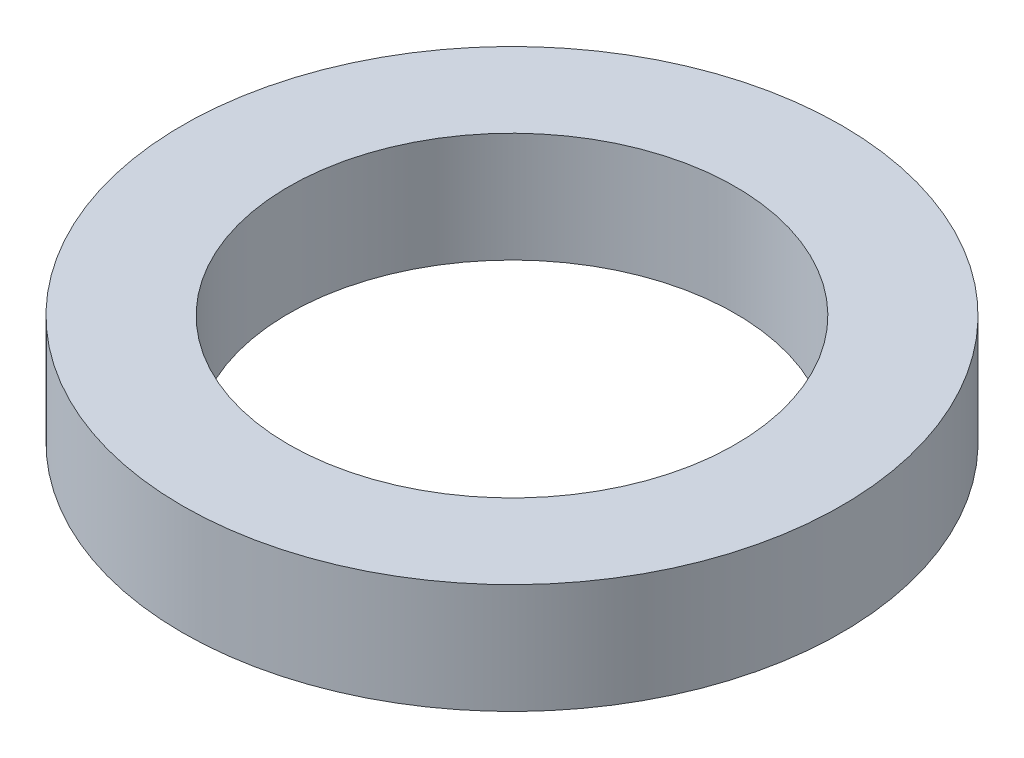
SolidWorks part; units mm, degrees
other "Front Wheel Spacer"
ref_plane "Front Plane" through (0, 0, 0) normal (0, 0, 1) x (1, 0, 0)
ref_plane "Top Plane" through (0, 0, 0) normal (0, 1, 0) x (1, 0, 0)
ref_plane "Right Plane" through (0, 0, 0) normal (1, 0, 0) x (0, 0, -1)
sketch3d "Spacer stock sketch datum points"
  point P0 (-19.0092, -218, -53.2449)
  point P1 (-9.0092, -218, -53.2449)
  point P2 (-19.0092, -218, -63.2449)
ref_plane "Spacer stock sketch plane" through (0, -218, 0) normal (0, 1, 0) x (1, 0, 0)
sketch "Spacer stock sketch" plane through (0, -218, 0) normal (0, 1, 0) x (1, 0, 0)
  circle A0 centre (-19.0092, 53.2449) radius 9
extrude "Spacer stock" add sketch "Spacer stock sketch" along normal blind 3 separate body
sketch3d "Axle running clearance sketch datum points"
  point P0 (-19.0092, -218.1, -53.2449)
  point P1 (-9.0092, -218.1, -53.2449)
  point P2 (-19.0092, -218.1, -63.2449)
ref_plane "Axle running clearance sketch plane" through (0, -218.1, 0) normal (0, 1, 0) x (1, 0, 0)
sketch "Axle running clearance sketch" plane through (0, -218.1, 0) normal (0, 1, 0) x (1, 0, 0)
  circle A0 centre (-19.0092, 53.2449) radius 6.1
extrude "Axle running clearance" cut sketch "Axle running clearance sketch" along normal blind 3.2
